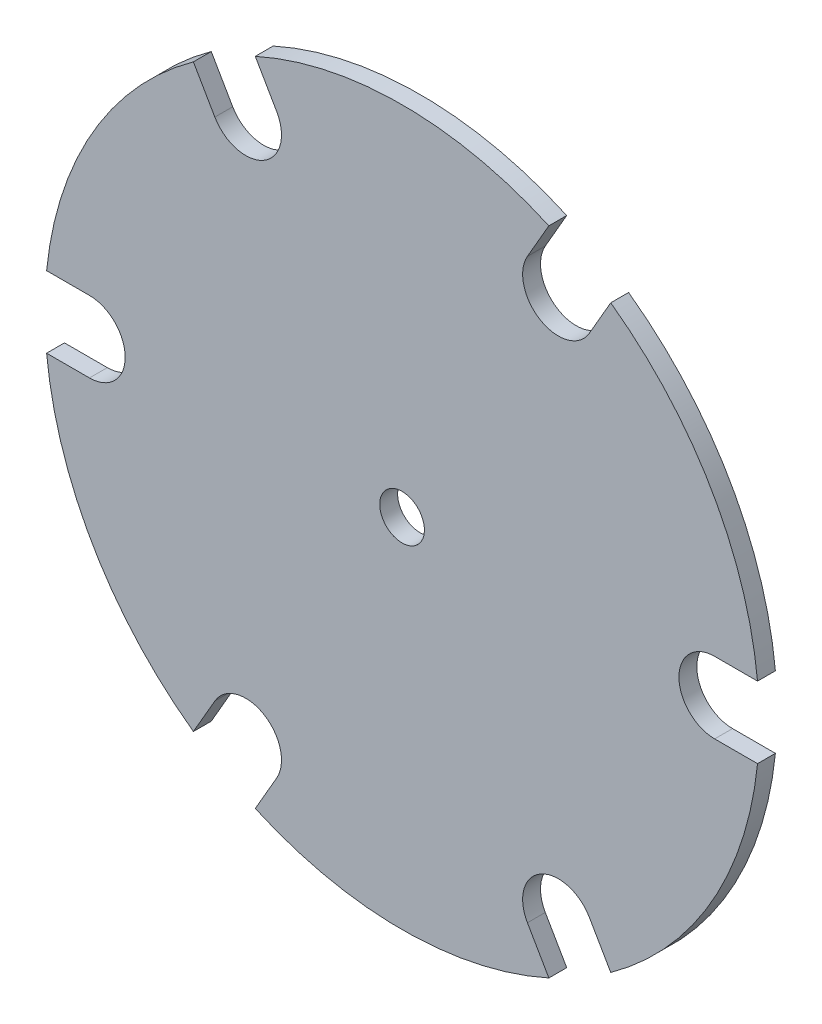
SolidWorks part; units mm, degrees
ref_plane "前视基准面" through (0, 0, 0) normal (0, 0, 1) x (1, 0, 0)
ref_plane "上视基准面" through (0, 0, 0) normal (0, 1, 0) x (1, 0, 0)
ref_plane "右视基准面" through (0, 0, 0) normal (1, 0, 0) x (0, 0, -1)
sketch "草图1" plane through (0, 0, 0) normal (0, 0, 1) x (1, 0, 0)
  line L0 (-35, 4) -> (-39.7995, 4)
  line L1 (-35, -4) -> (-39.7995, -4)
  line L2 (-14.0359, 32.3109) -> (-16.4356, 36.4674)
  line L3 (-20.9641, 28.3109) -> (-23.3639, 32.4674)
  line L4 (20.9641, 28.3109) -> (23.3639, 32.4674)
  line L5 (14.0359, 32.3109) -> (16.4356, 36.4674)
  line L6 (35, -4) -> (39.7995, -4)
  line L7 (35, 4) -> (39.7995, 4)
  line L8 (14.0359, -32.3109) -> (16.4356, -36.4674)
  line L9 (20.9641, -28.3109) -> (23.3639, -32.4674)
  line L10 (-20.9641, -28.3109) -> (-23.3639, -32.4674)
  line L11 (-14.0359, -32.3109) -> (-16.4356, -36.4674)
  arc A0 (-39.7995, -4) -> (-23.3639, -32.4674) centre (0, 0) ccw
  arc A1 (-35, -4) -> (-35, 4) centre (-35, 0) ccw
  arc A2 (-20.9641, 28.3109) -> (-14.0359, 32.3109) centre (-17.5, 30.3109) ccw
  arc A3 (14.0359, 32.3109) -> (20.9641, 28.3109) centre (17.5, 30.3109) ccw
  arc A4 (35, 4) -> (35, -4) centre (35, 0) ccw
  arc A5 (20.9641, -28.3109) -> (14.0359, -32.3109) centre (17.5, -30.3109) ccw
  arc A6 (-14.0359, -32.3109) -> (-20.9641, -28.3109) centre (-17.5, -30.3109) ccw
  arc A7 (-23.3639, 32.4674) -> (-39.7995, 4) centre (0, 0) ccw
  arc A8 (16.4356, 36.4674) -> (-16.4356, 36.4674) centre (0, 0) ccw
  arc A9 (39.7995, 4) -> (23.3639, 32.4674) centre (0, 0) ccw
  arc A10 (-16.4356, -36.4674) -> (16.4356, -36.4674) centre (0, 0) ccw
  arc A11 (23.3639, -32.4674) -> (39.7995, -4) centre (0, 0) ccw
  circle A12 centre (0, 0) radius 2.5
  point P35 (0, 0)
  dimension "D1" = 80
  dimension "D2" = 35
  dimension "D4" = 4
  dimension "D5" = 5
  dimension "D3" = 6
extrude "凸台-拉伸1" add sketch "草图1" along normal blind 2
